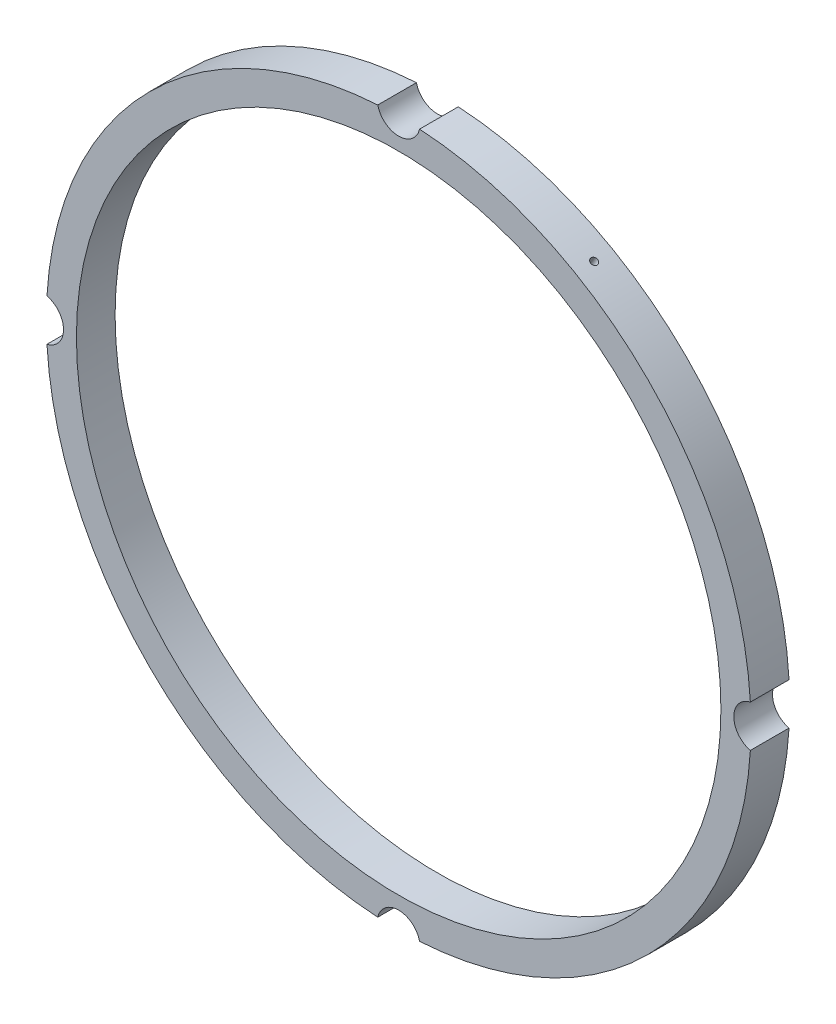
SolidWorks part; units mm, degrees
ref_plane "Front Plane" through (0, 0, 0) normal (0, 0, 1) x (1, 0, 0)
ref_plane "Top Plane" through (0, 0, 0) normal (0, 1, 0) x (1, 0, 0)
ref_plane "Right Plane" through (0, 0, 0) normal (1, 0, 0) x (0, 0, -1)
sketch "Sketch1" plane through (0, 0, 0) normal (0, 0, 1) x (1, 0, 0)
  circle A0 centre (0, 0) radius 75
  circle A1 centre (0, 0) radius 82
extrude "Boss-Extrude1" add sketch "Sketch1" along normal blind 9
sketch "Sketch2" plane through (0, 0, 9) normal (0, 0, 1) x (1, 0, 0)
  circle A0 centre (0, 83) radius 5
extrude "Cut-Extrude1" cut sketch "Sketch2" against normal through all
pattern_circular "CirPattern1" count 4 every 90 about axis through (0, 0, 0) along (0, 0, 1) of "Cut-Extrude1"
hole_wizard "M2x0.4 Tapped Hole1" positions "3DSketch1" profile "Sketch3" tap size "M2x0.4" standard "ANSI Metric"
sketch3d "3DSketch1"
  point P0 (41, 71.0141, 4.5)
sketch "Sketch3" plane through (41, 71.0141, 4.5) normal (0, 0, 1) x (-0.866, 0.5, 0)
  line L0 (0, 0) -> (0, 10.4807)
  line L1 (0, 10.4807) -> (0.8, 10)
  line L2 (0.8, 10) -> (0.8, 0)
  line L5 (0.8, 0) -> (0, 0)
  line L10 (0, 10.4807) -> (-0.8, 10) construction
  line L11 (0, -6.35) -> (0, 107.95) construction
  dimension "Tap Drill Dia." = 1.6
  dimension "Tap Drill Depth" = 10
  dimension "Drill Angle" = 118
cosmetic thread "Hole Thread1" parameters "D1"=4, "D2"=2
